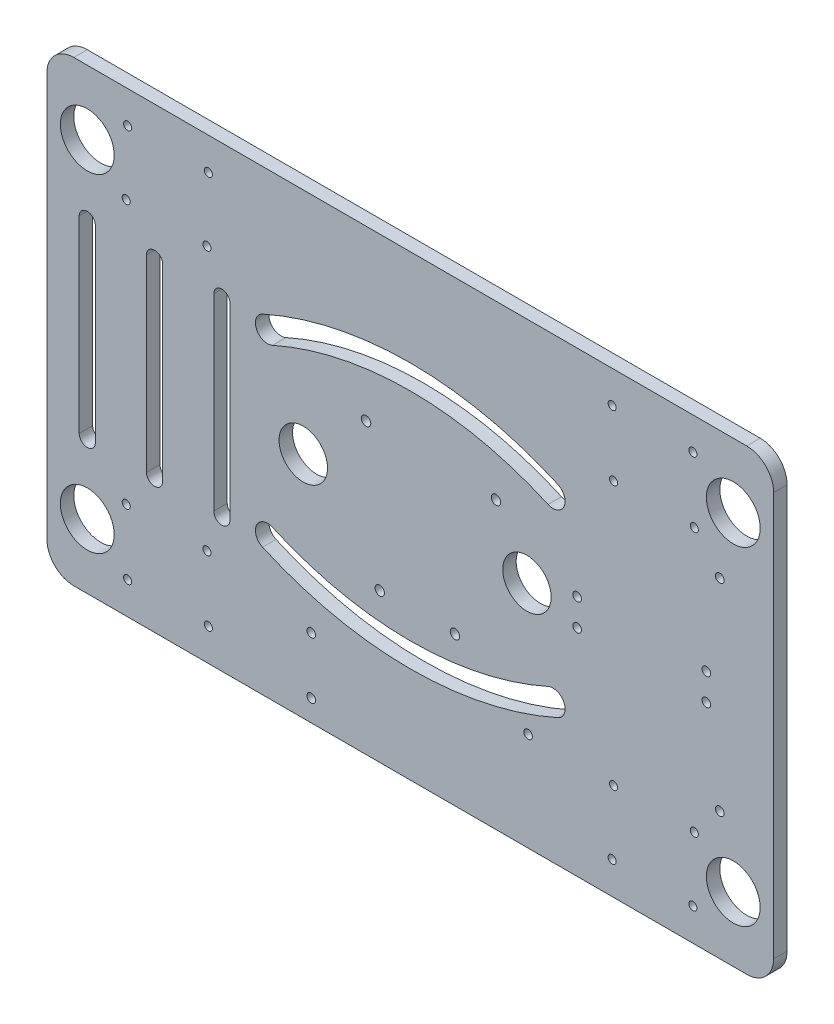
SolidWorks part; units mm, degrees
ref_plane "前视基准面" through (0, 0, 0) normal (0, 0, 1) x (1, 0, 0)
ref_plane "上视基准面" through (0, 0, 0) normal (0, 1, 0) x (1, 0, 0)
ref_plane "右视基准面" through (0, 0, 0) normal (1, 0, 0) x (0, 0, -1)
sketch "草图2" plane through (0, 0, 0) normal (0, 0, 1) x (1, 0, 0)
  line L0 (-175.5422, -0.0669) -> (94.4557, -0.0669) construction
  line L1 (-165.5422, 84.9331) -> (84.4578, 84.9331)
  line L2 (-175.5422, 74.9331) -> (-175.5422, -75.0669)
  line L3 (-165.5422, -85.0669) -> (84.4578, -85.0669)
  line L4 (94.4578, 74.9331) -> (94.4578, -75.0669)
  line L5 (-175.5422, 84.9331) -> (94.4578, -85.0669) construction
  line L6 (-175.5422, -85.0669) -> (94.4578, 84.9331) construction
  line L7 (-40.5422, 84.9331) -> (-40.5422, -85.2471) construction
  line L8 (-51.8845, -29.7647) -> (-23.9445, -29.7647) construction
  line L9 (-135.5422, 34.9132) -> (-135.5422, -35.047) construction
  line L10 (-77.3304, -56.0669) -> (-77.3304, -77.0669) construction
  line L11 (-160.5422, 34.9132) -> (-160.5422, -35.047) construction
  line L12 (-157.5422, 34.9132) -> (-157.5422, -35.047)
  line L13 (-163.5422, 34.9132) -> (-163.5422, -35.047)
  line L14 (-132.5422, 34.9132) -> (-132.5422, -35.047)
  line L17 (-138.5422, 34.9132) -> (-138.5422, -35.047)
  line L20 (-110.5422, 34.9132) -> (-110.5422, -35.047) construction
  line L21 (-107.5422, 34.9132) -> (-107.5422, -35.047)
  line L22 (-113.5422, 34.9132) -> (-113.5422, -35.047)
  arc A0 (-175.5422, 74.9331) -> (-165.5422, 84.9331) centre (-165.5422, 74.9331) cw
  arc A1 (94.4578, 74.9331) -> (84.4578, 84.9331) centre (84.4578, 74.9331) ccw
  arc A2 (84.4578, -85.0669) -> (94.4578, -75.0669) centre (84.4578, -75.0669) ccw
  arc A3 (-165.5422, -85.0669) -> (-175.5422, -75.0669) centre (-165.5422, -75.0669) cw
  circle A4 centre (-145.5422, 72.9331) radius 1.5
  circle A5 centre (-115.5422, 72.9331) radius 1.5
  circle A6 centre (-146.0658, 48.9331) radius 1.5
  circle A7 centre (-116.0658, 48.9331) radius 1.5
  circle A8 centre (-116.0658, -49.0669) radius 1.5
  circle A9 centre (-115.5422, -73.0669) radius 1.5
  circle A10 centre (-145.5422, -73.0669) radius 1.5
  circle A11 centre (-146.0658, -49.0669) radius 1.5
  circle A12 centre (64.9814, 48.9331) radius 1.5
  circle A13 centre (34.9814, 48.9331) radius 1.5
  circle A14 centre (34.4578, 72.9331) radius 1.5
  circle A15 centre (64.4578, 72.9331) radius 1.5
  circle A16 centre (34.4578, -73.0669) radius 1.5
  circle A17 centre (34.9814, -49.0669) radius 1.5
  circle A18 centre (64.9814, -49.0669) radius 1.5
  circle A19 centre (64.4578, -73.0669) radius 1.5
  circle A20 centre (74.4578, 37.4331) radius 1.6
  circle A21 centre (74.4578, -37.5669) radius 1.6
  circle A22 centre (69.4578, 4.9331) radius 1.6
  circle A23 centre (21.4578, 4.9331) radius 1.6
  circle A24 centre (69.4578, -5.0669) radius 1.6
  circle A25 centre (21.4578, -5.0669) radius 1.6
  circle A26 centre (-23.9445, -29.7647) radius 1.75
  circle A27 centre (-51.8845, -29.7647) radius 1.75
  circle A28 centre (-8.7045, 21.0353) radius 1.75
  circle A29 centre (-56.9645, 22.3053) radius 1.75
  circle A30 centre (2.7998, -0.0669) radius 9
  circle A31 centre (-80.2957, -0.0669) radius 9
  circle A32 centre (-160.5422, 60.9331) radius 10
  circle A33 centre (-160.5422, -61.0669) radius 10
  circle A34 centre (-77.3304, -56.0669) radius 1.6
  circle A35 centre (-77.3304, -77.0669) radius 1.6
  circle A36 centre (3.2297, -48.443) radius 1.6
  arc A37 (-157.5422, 34.9132) -> (-163.5422, 34.9132) centre (-160.5422, 34.9132) ccw
  arc A38 (-163.5422, -35.047) -> (-157.5422, -35.047) centre (-160.5422, -35.047) ccw
  arc A43 (12.4904, -33.4579) -> (-93.5749, -33.4579) centre (-40.5422, 84.9331) cw construction
  arc A44 (-95.4145, -37.5647) -> (14.3301, -37.5647) centre (-40.5422, 84.9331) ccw
  arc A45 (-91.7353, -29.3511) -> (10.6508, -29.3511) centre (-40.5422, 84.9331) ccw
  arc A46 (-91.7353, -29.3511) -> (-95.4145, -37.5647) centre (-93.5749, -33.4579) ccw
  arc A47 (14.3301, -37.5647) -> (10.6508, -29.3511) centre (12.4904, -33.4579) ccw
  arc A48 (12.4904, 33.324) -> (-93.5749, 33.324) centre (-40.5422, -85.0669) ccw construction
  arc A49 (-95.4145, 37.4308) -> (14.3301, 37.4308) centre (-40.5422, -85.0669) cw
  arc A50 (-91.7353, 29.2172) -> (10.6508, 29.2172) centre (-40.5422, -85.0669) cw
  arc A51 (-91.7353, 29.2172) -> (-95.4145, 37.4308) centre (-93.5749, 33.324) cw
  arc A52 (14.3301, 37.4308) -> (10.6508, 29.2172) centre (12.4904, 33.324) cw
  circle A53 centre (79.4578, -61.0669) radius 10
  circle A54 centre (79.4578, 60.9331) radius 10
  arc A55 (-132.5422, 34.9132) -> (-138.5422, 34.9132) centre (-135.5422, 34.9132) ccw
  arc A56 (-138.5422, -35.047) -> (-132.5422, -35.047) centre (-135.5422, -35.047) ccw
  arc A57 (-107.5422, 34.9132) -> (-113.5422, 34.9132) centre (-110.5422, 34.9132) ccw
  arc A58 (-113.5422, -35.047) -> (-107.5422, -35.047) centre (-110.5422, -35.047) ccw
  point P0 (-40.5422, -0.0669)
  point P30 (-40.5422, -0.0669)
  point P90 (-160.5422, -0.0669)
  point P100 (-135.5422, -0.0669)
  point P107 (-110.5422, -0.0669)
  point P111 (-40.5422, -44.7931)
  point P119 (-40.5422, 44.6592)
  dimension "D1" = 10
  dimension "D2" = 10
  dimension "D3" = 10
  dimension "D4" = 10
  dimension "D5" = 12
  dimension "D7" = 30
  dimension "D8" = 24
  dimension "D13" = 47.5
  dimension "D15" = 25
  dimension "D18" = 27.94
  dimension "D22" = 24
  dimension "D24" = 21
  dimension "D25" = 80.92
  dimension "D27" = 2
  dimension "D29" = 5.08
  dimension "D6" = 30
  dimension "D9" = 24
  dimension "D10" = 12
  dimension "D11" = 150
  dimension "D12" = 250
  dimension "D14" = 20
  dimension "D16" = 80
  dimension "D17" = 48
  dimension "D19" = 52.07
  dimension "D20" = 50.8
  dimension "D21" = 15.24
  dimension "D23" = 15
  dimension "D26" = 8
  dimension "D30" = 48.26
  dimension "D31" = 10
  dimension "D28" = 2
extrude "凸台-拉伸1" add sketch "草图2" along normal blind 5
